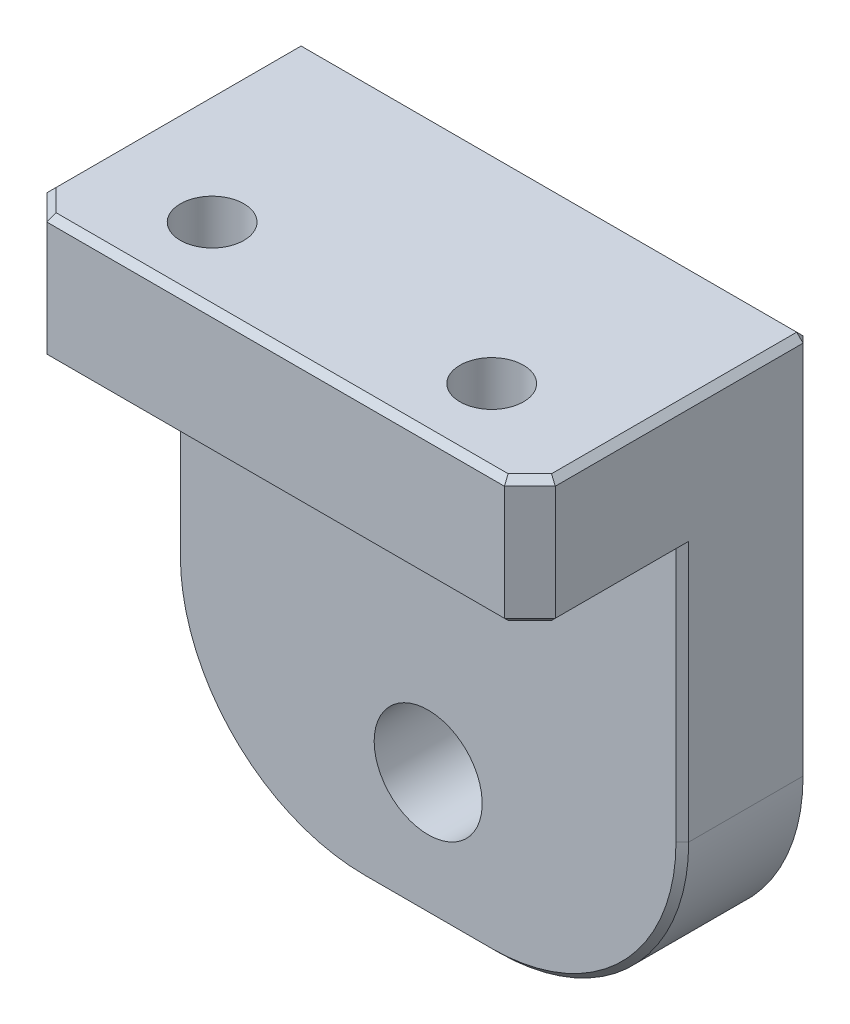
SolidWorks part; units mm, degrees
ref_plane "前视基准面" through (0, 0, 0) normal (0, 0, 1) x (1, 0, 0)
ref_plane "上视基准面" through (0, 0, 0) normal (0, 1, 0) x (1, 0, 0)
ref_plane "右视基准面" through (0, 0, 0) normal (1, 0, 0) x (0, 0, -1)
sketch "草图1" plane through (0, 0, 0) normal (0, 0, 1) x (1, 0, 0)
  line L1 (-20, -22.5) -> (20, -22.5)
  line L2 (-20, -22.5) -> (-20, 22.5)
  line L3 (-20, 22.5) -> (20, 22.5)
  line L4 (20, -22.5) -> (20, 22.5)
  line L5 (-20, -22.5) -> (20, 22.5) construction
  line L6 (-20, 22.5) -> (20, -22.5) construction
  point P0 (0, 0)
  dimension "D1" = 45
  dimension "D2" = 40
extrude "凸台-拉伸1" add sketch "草图1" along normal mid plane 10
sketch "草图2" plane through (0, 0, 5) normal (0, 0, 1) x (1, 0, 0)
  line L0 (20, -22.5) -> (20, 22.5) construction
  line L1 (-20, 22.5) -> (20, 22.5)
  line L2 (-20, 22.5) -> (-20, 12.5)
  line L3 (-20, 12.5) -> (20, 12.5)
  line L4 (20, 22.5) -> (20, 12.5)
  dimension "D1" = 10
extrude "凸台-拉伸2" add sketch "草图2" along normal blind 12
sketch "草图3" plane through (0, 0, -5) normal (0, 0, -1) x (-1, 0, 0)
  line L0 (0, 22.5) -> (0, -12.5)
  line L1 (-20, 22.5) -> (20, 22.5) construction
  dimension "D1" = 35
hole_wizard "M10 螺纹孔1" positions "草图6" profile "草图7" tap size "M10" standard "ISO" end condition through all
sketch "草图6" plane through (0, 0, -5) normal (0, 0, -1) x (-1, 0, 0)
  point P0 (0, -12.5)
sketch "草图7" plane through (0, -12.5, -5) normal (1, 0, 0) x (0, 1, 0)
  line L0 (0, 0) -> (0, 22)
  line L1 (0, 22) -> (4.25, 22)
  line L2 (4.25, 22) -> (4.25, 0)
  line L5 (4.25, 0) -> (0, 0)
  line L11 (0, -6.35) -> (0, 107.95) construction
  dimension "通孔螺纹孔钻头直径" = 8.5
  dimension "通孔螺纹孔钻头深度" = 22
cosmetic thread "孔螺蚊线1" parameters "D2"=10
sketch "草图8" plane through (0, 12.5, 0) normal (0, -1, 0) x (1, 0, 0)
  line L0 (0, 17) -> (0, 5) construction
  line L1 (-20, 17) -> (20, 17) construction
  line L2 (-20, 5) -> (20, 5) construction
  line L3 (11, 11) -> (-11, 11) construction
  circle A0 centre (11, 11) radius 3.5
  circle A1 centre (-11, 11) radius 3.5
  point P9 (0, 11)
  dimension "D2" = 7
  dimension "D1" = 22
hole_wizard "M6 螺纹孔1" positions "草图9" profile "草图10" tap size "M6" standard "ISO" end condition through all
sketch "草图9" plane through (0, 12.5, 0) normal (0, -1, 0) x (-1, 0, 0)
  point P0 (-11, -11)
  point P3 (11, -11)
sketch "草图10" plane through (11, 12.5, 11) normal (1, 0, 0) x (0, 0, -1)
  line L0 (0, 0) -> (0, 10)
  line L1 (0, 10) -> (2.5, 10)
  line L2 (2.5, 10) -> (2.5, 0)
  line L5 (2.5, 0) -> (0, 0)
  line L11 (0, -6.35) -> (0, 107.95) construction
  dimension "通孔螺纹孔钻头直径" = 5
  dimension "通孔螺纹孔钻头深度" = 10
cosmetic thread "孔螺蚊线2" parameters "D2"=6
cosmetic thread "孔螺蚊线3" parameters "D2"=6
fillet "圆角1" radius 15 2 edges at (-20, -22.5, 0) (20, -22.5, 0)
chamfer "倒角1" distance 2 angle 45 2 edges at (-20, 17.5, 17) (20, 17.5, 17)
chamfer "倒角2" distance 0.5 angle 45 21 edges at (-20, 7.5, -5) (-15.6066, -18.1066, -5) (0, -22.5, -5) (15.6066, -18.1066, -5) (20, 7.5, -5) (0, 22.5, -5) (-20, 12.5, 10) (20, 12.5, 10) (0, 22.5, 17) (-20, 2.5, 5) (-15.6066, -18.1066, 5) (0, -22.5, 5) (20, 2.5, 5) (15.6066, -18.1066, 5) (-20, 22.5, 5) (20, 22.5, 5) (0, 12.5, 17) (-19, 12.5, 16) (19, 12.5, 16) (-19, 22.5, 16) (19, 22.5, 16)
